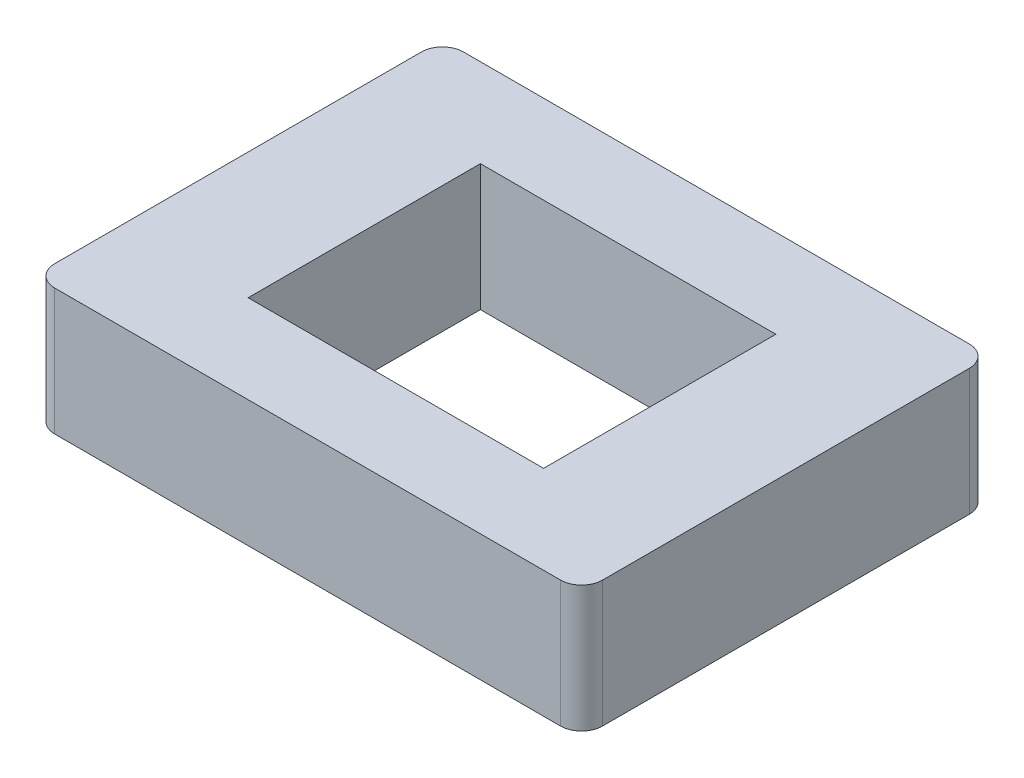
SolidWorks part; units mm, degrees
material "Plain Carbon Steel"
ref_plane "Front Plane" through (0, 0, 0) normal (0, 0, 1) x (1, 0, 0)
ref_plane "Top Plane" through (0, 0, 0) normal (0, 1, 0) x (1, 0, 0)
ref_plane "Right Plane" through (0, 0, 0) normal (1, 0, 0) x (0, 0, -1)
sketch "Sketch1" plane through (0, 0, 0) normal (0, 1, 0) x (1, 0, 0)
  line L1 (-65, -48.5) -> (65, -48.5)
  line L2 (-65, -48.5) -> (-65, 48.5)
  line L3 (-65, 48.5) -> (65, 48.5)
  line L4 (65, -48.5) -> (65, 48.5)
  line L5 (-65, -48.5) -> (65, 48.5) construction
  line L6 (-65, 48.5) -> (65, -48.5) construction
  point P0 (0, 0)
  dimension "D1" = 130
  dimension "D2" = 97
extrude "Boss-Extrude1" add sketch "Sketch1" against normal blind 30
fillet "Fillet1" radius 5 4 edges at (-65, -15, -48.5) (-65, -15, 48.5) (65, -15, -48.5) (65, -15, 48.5)
sketch "Sketch2" plane through (0, -30, 0) normal (0, 1, 0) x (1, 0, 0)
  line L8 (35.05, 27.55) -> (-35.05, 27.55)
  line L9 (-35.05, 27.55) -> (-35.05, -27.55)
  line L10 (-35.05, -27.55) -> (35.05, -27.55)
  line L11 (35.05, -27.55) -> (35.05, 27.55)
  point P2 (-35.05, 0)
  point P4 (0, -27.55)
  dimension "D1" = 70.1
  dimension "D2" = 55.1
extrude "Cut-Extrude3" cut sketch "Sketch2" along normal through all
